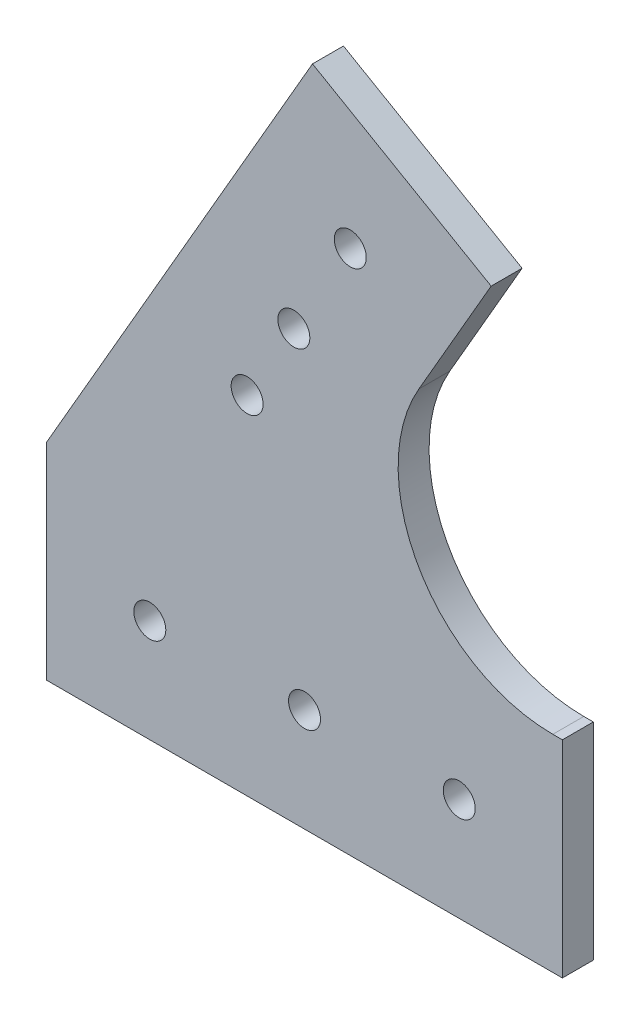
SolidWorks part; units mm, degrees
ref_plane "前视基准面" through (0, 0, 0) normal (0, 0, 1) x (1, 0, 0)
ref_plane "上视基准面" through (0, 0, 0) normal (0, 1, 0) x (1, 0, 0)
ref_plane "右视基准面" through (0, 0, 0) normal (1, 0, 0) x (0, 0, -1)
sketch "草图1" plane through (0, 0, 0) normal (0, 0, 1) x (1, 0, 0)
  line L0 (-25, 10) -> (0.7735, 54.641)
  line L1 (-25, 10) -> (25, 10)
  line L2 (-25, 10) -> (-25, -10)
  line L3 (-25, -10) -> (25, -10)
  line L4 (25, 10) -> (25, -10)
  line L5 (-25, 10) -> (25, -10) construction
  line L6 (-25, -10) -> (25, 10) construction
  line L7 (-1.906, 10) -> (18.094, 44.641)
  line L8 (18.094, 44.641) -> (0.7735, 54.641)
  line L9 (-1000, 0) -> (49000, 0) construction
  line L10 (9.4338, 49.641) -> (-13.453, 10) construction
  line L11 (-1.906, 10) -> (-19.2265, 20) construction
  line L12 (0, 0) -> (0, 5.5232) construction
  circle A0 centre (-5.5662, 23.6603) radius 1.55
  circle A1 centre (4.4338, 40.9808) radius 1.55
  circle A3 centre (15, 0) radius 1.55
  circle A4 centre (-15, 0) radius 1.55
  circle A5 centre (0, 0) radius 1.55
  circle A6 centre (-1.0359, 31.5071) radius 1.55
  point P0 (0, 0)
  dimension "D6" = 3.1
  dimension "D7" = 3.1
  dimension "D9" = 20
  dimension "D10" = 3.1
  dimension "D11" = 3.1
  dimension "D12" = 15
  dimension "D13" = 3.1
  dimension "D1" = 20
  dimension "D2" = 50
  dimension "D3" = 60
  dimension "D4" = 20
  dimension "D5" = 40
  dimension "D8" = 10
extrude "凸台-拉伸1" add sketch "草图1" along normal blind 3 contours L7 L8 L0 L1 | L4 L1 L2 L3
fillet "圆角1" radius 15 1 edges at (-1.906, 10, 1.5)
